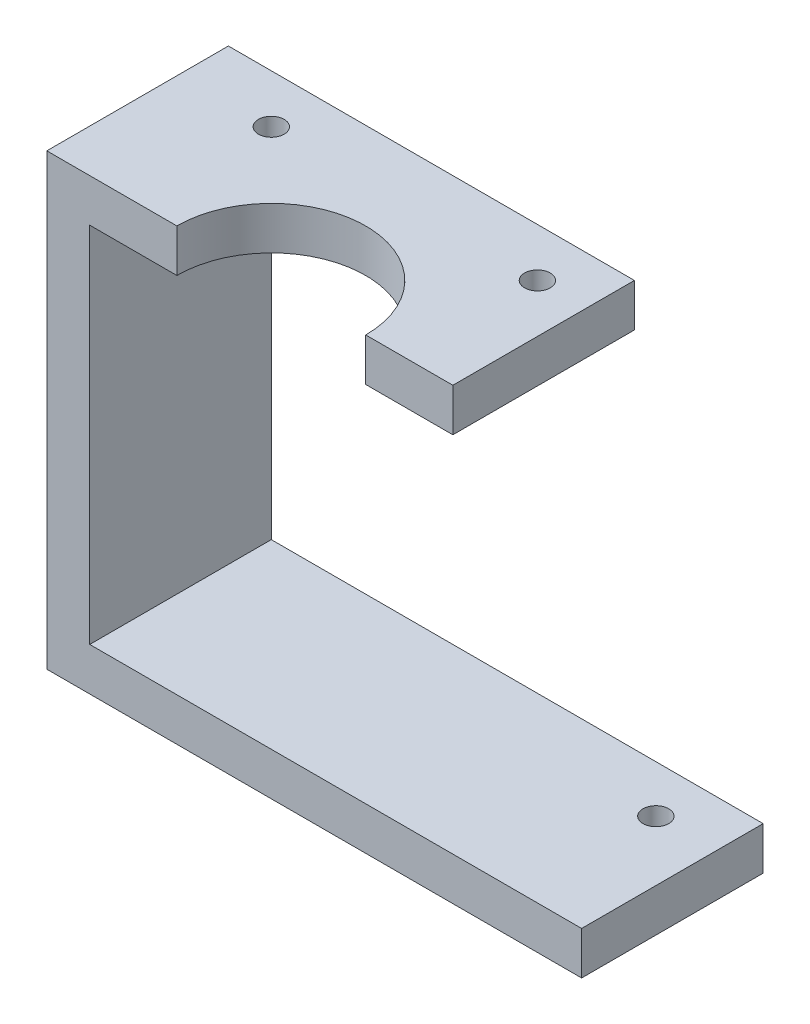
SolidWorks part; units mm, degrees
ref_plane "Front Plane" through (0, 0, 0) normal (0, 0, 1) x (1, 0, 0)
ref_plane "Top Plane" through (0, 0, 0) normal (0, 1, 0) x (1, 0, 0)
ref_plane "Right Plane" through (0, 0, 0) normal (1, 0, 0) x (0, 0, -1)
sketch "Sketch1" plane through (0, 0, 0) normal (0, 1, 0) x (1, 0, 0)
  line L1 (0, 0) -> (62.3, 0)
  line L2 (0, 0) -> (0, 42.3)
  line L3 (0, 42.3) -> (62.3, 42.3)
  line L4 (62.3, 0) -> (62.3, 42.3)
  dimension "D2" = 62.3
extrude "Boss-Extrude1" add sketch "Sketch1" along normal blind 5
sketch "Sketch2" plane through (0, 5, 0) normal (0, 1, 0) x (1, 0, 0)
  line L0 (0, 0) -> (62.3, 0) construction
  line L1 (0, 42.3) -> (5, 42.3)
  line L2 (0, 42.3) -> (0, 0)
  line L3 (0, 0) -> (5, 0)
  line L4 (5, 42.3) -> (5, 0)
  dimension "D1" = 5
extrude "Boss-Extrude2" add sketch "Sketch2" along normal blind 42.3
sketch "Sketch3" plane through (0, 47.3, 0) normal (0, 1, 0) x (1, 0, 0)
  line L1 (0, 42.3) -> (47.3, 42.3)
  line L2 (0, 42.3) -> (0, 0)
  line L3 (0, 0) -> (47.3, 0)
  line L4 (47.3, 42.3) -> (47.3, 0)
  circle A0 centre (26.15, 21.15) radius 11
  point P8 (0.9359, 65.29)
  dimension "D1" = 22
  dimension "D2" = 26.15
  dimension "D3" = 21.15
  dimension "D4" = 47.3
extrude "Boss-Extrude3" add sketch "Sketch3" along normal blind 5 contours L2 L1 L4 L3 | A0
sketch "Sketch4" plane through (0, 52.3, 0) normal (0, 1, 0) x (1, 0, 0)
  circle A0 centre (41.65, 36.65) radius 1.5
  circle A1 centre (26.15, 21.15) radius 11 construction
  circle A2 centre (10.65, 36.65) radius 1.5
  circle A3 centre (10.65, 5.65) radius 1.5
  circle A4 centre (41.65, 5.65) radius 1.5
  dimension "D1" = 15.5
  dimension "D3" = 3
  dimension "D4" = 31
  dimension "D5" = 31
  dimension "D2" = 15.5
extrude "Cut-Extrude1" cut sketch "Sketch4" against normal blind 5
sketch "Sketch5" plane through (0, 5, 0) normal (0, 1, 0) x (1, 0, 0)
  line L0 (62.3, 42.3) -> (5, 42.3) construction
  line L1 (5, 0) -> (62.3, 0) construction
  line L2 (62.3, 0) -> (62.3, 42.3) construction
  circle A0 centre (55.3, 5.5) radius 1.5
  circle A1 centre (55.3, 36.8) radius 1.5
  dimension "D1" = 3
  dimension "D2" = 5.5
  dimension "D3" = 5.5
  dimension "D4" = 7
  dimension "D5" = 7
extrude "Cut-Extrude2" cut sketch "Sketch5" against normal blind 5
ref_plane "Plane2" through (0, 0, -21.15) normal (0, 0, -1) x (-1, 0, 0)
sketch "Sketch6" plane through (0, 0, -21.15) normal (0, 0, -1) x (-1, 0, 0)
  line L1 (-64.1902, 54.102) -> (2.2136, 54.102)
  line L2 (-64.1902, 54.102) -> (-64.1902, -1.4159)
  line L3 (-64.1902, -1.4159) -> (2.2136, -1.4159)
  line L4 (2.2136, 54.102) -> (2.2136, -1.4159)
extrude "Cut-Extrude3" cut sketch "Sketch6" against normal blind 40
